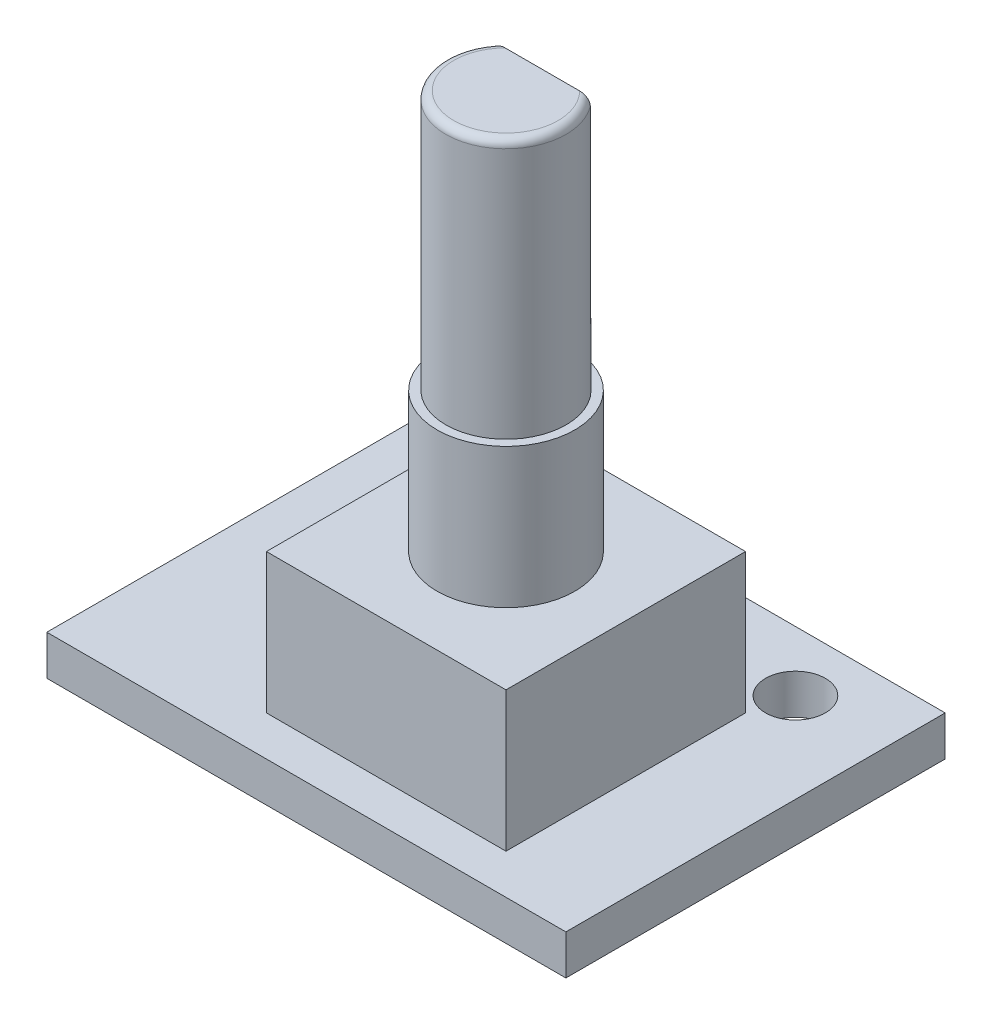
SolidWorks part; units mm, degrees
ref_plane "Front Plane" through (0, 0, 0) normal (0, 0, 1) x (1, 0, 0)
ref_plane "Top Plane" through (0, 0, 0) normal (0, 1, 0) x (1, 0, 0)
ref_plane "Right Plane" through (0, 0, 0) normal (1, 0, 0) x (0, 0, -1)
sketch "Sketch1" plane through (0, 0, 0) normal (0, 1, 0) x (1, 0, 0)
  line L1 (0, 0) -> (26, 0)
  line L2 (0, 0) -> (0, 19)
  line L3 (0, 19) -> (26, 19)
  line L4 (26, 0) -> (26, 19)
  dimension "D1" = 19
  dimension "D2" = 26
extrude "Boss-Extrude1" add sketch "Sketch1" along normal blind 2
sketch "Sketch2" plane through (0, 2, 0) normal (0, 1, 0) x (1, 0, 0)
  line L0 (26, 19) -> (0, 19) construction
  line L1 (21, 2) -> (9, 2)
  line L2 (21, 2) -> (21, 14)
  line L3 (21, 14) -> (9, 14)
  line L4 (9, 2) -> (9, 14)
  line L5 (26, 0) -> (26, 19) construction
  dimension "D1" = 5
  dimension "D2" = 5
  dimension "D3" = 12
  dimension "D4" = 12
extrude "Boss-Extrude2" add sketch "Sketch2" along normal blind 7
sketch "Sketch3" plane through (0, 9, 0) normal (0, 1, 0) x (1, 0, 0)
  line L0 (21, 2) -> (21, 14) construction
  line L1 (21, 14) -> (9, 14) construction
  circle A0 centre (15, 8) radius 3.45
  dimension "D1" = 6.9
  dimension "D2" = 6
  dimension "D3" = 6
extrude "Boss-Extrude3" add sketch "Sketch3" along normal blind 7
sketch "Sketch4" plane through (0, 16, 0) normal (0, 1, 0) x (1, 0, 0)
  circle A0 centre (15, 8) radius 3.0132
extrude "Boss-Extrude4" add sketch "Sketch4" along normal blind 13
sketch "Sketch5" plane through (0, 29, 0) normal (0, 1, 0) x (1, 0, 0)
  line L0 (12.6033, 9.8263) -> (17.3967, 9.8263)
  circle A0 centre (15, 8) radius 3.0132 construction
  arc A1 (12.6033, 9.8263) -> (17.3967, 9.8263) centre (15, 8) cw
  circle M2 centre (15, 8) radius 3.0132
  dimension "D1" = 4.8395
extrude "Cut-Extrude1" cut sketch "Sketch5" against normal blind 10 contours L0 M2
fillet "Fillet1" radius 0.4 1 edges at (15, 29, -4.9868)
sketch "Sketch6" plane through (0, 2, 0) normal (0, 1, 0) x (1, 0, 0)
  line L0 (26, 0) -> (26, 19) construction
  line L1 (26, 19) -> (0, 19) construction
  circle A0 centre (21.5, 16) radius 1.5
  circle A1 centre (4.5, 16) radius 1.5
  dimension "D1" = 3
  dimension "D2" = 17
  dimension "D3" = 4.5
  dimension "D4" = 3
extrude "Cut-Extrude2" cut sketch "Sketch6" against normal through all
